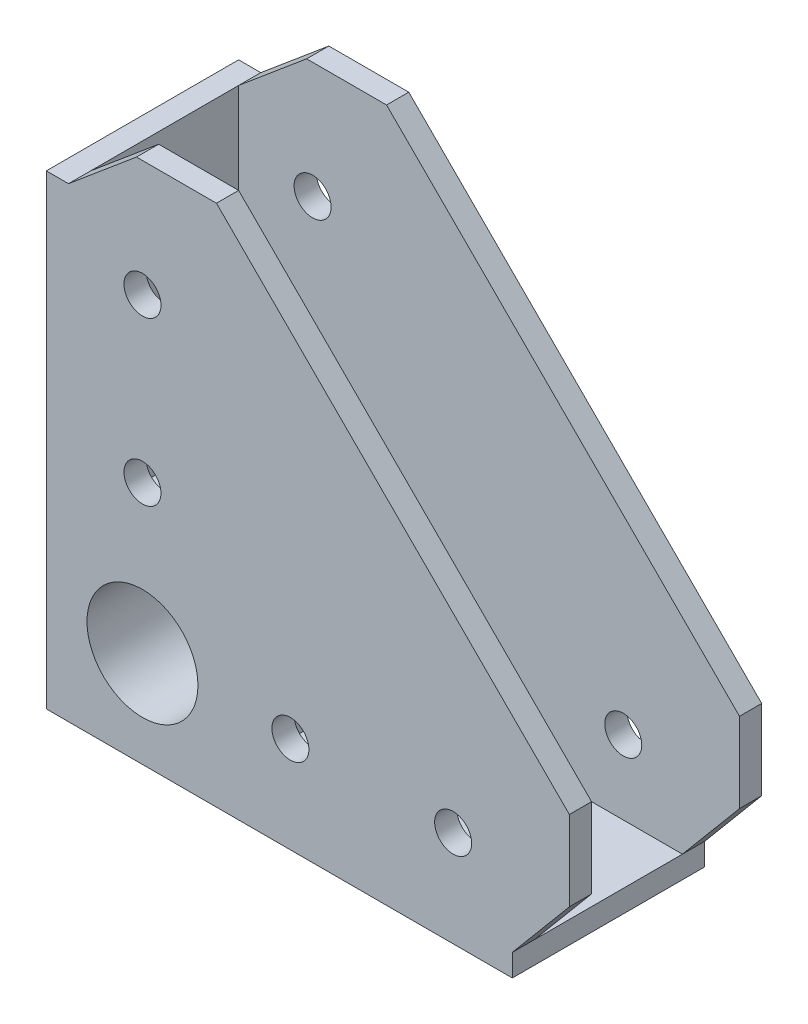
SolidWorks part; units mm, degrees
other "İşaretleme1"
sketch "Çizim10" plane through (57.7135, 57.7135, -3) normal (0.8319, 0.5548, -0.006) x (0.1401, -0.2205, -0.9653)
ref_plane "Ön Düzlem" through (0, 0, 0) normal (0, 0, 1) x (1, 0, 0)
ref_plane "Üst Düzlem" through (0, 0, 0) normal (0, 1, 0) x (1, 0, 0)
ref_plane "Sağ Düzlem" through (0, 0, 0) normal (1, 0, 0) x (0, 0, -1)
sketch "Çizim1" plane through (0, 0, 0) normal (0, 0, 1) x (1, 0, 0)
  line L0 (-21.4286, 0) -> (19.4898, 0) construction
  line L1 (0, 15.5102) -> (0, -19.1837) construction
  line L3 (-10, 10) -> (10, 10)
  line L4 (-10, 10) -> (-10, -10)
  line L5 (-10, -10) -> (10, -10)
  line L6 (10, 10) -> (10, -10)
  line L7 (-10, 10) -> (10, -10) construction
  line L8 (-10, -10) -> (10, 10) construction
  point P5 (0, 0)
  dimension "D1" = 20
  dimension "D2" = 20
extrude "Yükseklik-Ekstrüzyon1" add sketch "Çizim1" along normal blind 20
sketch "Çizim2" plane through (0, 0, 20) normal (0, 0, 1) x (1, 0, 0)
  line L0 (-10, -10) -> (-10, 10)
  line L1 (-10, 10) -> (-10, 50)
  line L2 (-10, -10) -> (10, -10)
  line L3 (10, -10) -> (50, -10)
  line L4 (-10, 50) -> (-0.8075, 57.7135)
  line L5 (50, -10) -> (57.7135, -0.8075)
  line L6 (57.7135, -0.8075) -> (57.7135, 10)
  line L7 (-0.8075, 57.7135) -> (10, 57.7135)
  line L8 (10, 57.7135) -> (57.7135, 10)
  dimension "D1" = 40
  dimension "D2" = 40
  dimension "D3" = 12
  dimension "D4" = 130
  dimension "D5" = 130
  dimension "D6" = 12
extrude "Yükseklik-Ekstrüzyon2" add sketch "Çizim2" along normal blind 3
sketch "Çizim3" plane through (0, 0, 0) normal (0, 0, -1) x (-1, 0, 0)
  line L0 (10, -10) -> (-50, -10)
  line L1 (-50, -10) -> (-57.7135, -0.8075)
  line L2 (-57.7135, -0.8075) -> (-57.7135, 10)
  line L3 (-57.7135, 10) -> (-10, 57.7135)
  line L4 (-10, 57.7135) -> (0.8075, 57.7135)
  line L5 (0.8075, 57.7135) -> (10, 50)
  line L6 (10, 50) -> (10, -10)
extrude "Yükseklik-Ekstrüzyon3" add sketch "Çizim3" along normal blind 3
sketch "Çizim4" plane through (-10, 0, 0) normal (-1, 0, 0) x (0, 0, 1)
  line L0 (-3, -10) -> (23, -10)
  line L1 (23, -10) -> (23, 50)
  line L2 (23, 50) -> (-3, 50)
  line L3 (-3, 50) -> (-3, -10)
extrude "Yükseklik-Ekstrüzyon4" add sketch "Çizim4" along normal blind 3
sketch "Çizim5" plane through (0, -10, 0) normal (0, -1, 0) x (1, 0, 0)
  line L0 (-13, 23) -> (50, 23)
  line L1 (50, 23) -> (50, -3)
  line L2 (50, -3) -> (-13, -3)
  line L3 (-13, -3) -> (-13, 23)
extrude "Yükseklik-Ekstrüzyon5" add sketch "Çizim5" along normal blind 3
sketch "Çizim6" plane through (0, 0, 23) normal (0, 0, 1) x (1, 0, 0)
  circle A0 centre (0, 0) radius 7.5
  dimension "D3" = 15
extrude "Kes-Ekstrüzyon1" cut sketch "Çizim6" against normal through all
sketch "Çizim7" plane through (0, 0, -3) normal (0, 0, -1) x (-1, 0, 0)
  circle A1 centre (-20, 0) radius 2.5
  circle A2 centre (-42, 0) radius 2.5
  circle A3 centre (0, 20) radius 2.5
  circle A4 centre (0, 42) radius 2.5
  dimension "D1" = 5
  dimension "D2" = 5
  dimension "D3" = 5
  dimension "D4" = 5
  dimension "D5" = 20
  dimension "D6" = 22
  dimension "D7" = 20
  dimension "D8" = 22
extrude "Kes-Ekstrüzyon2" cut sketch "Çizim7" against normal blind 50
sketch "Çizim8" plane through (-10, 0, 0) normal (1, 0, 0) x (0, 0, -1)
  line L0 (-20, 10) -> (0, 10) construction
  circle A0 centre (-10, 20) radius 1.9247
  circle A1 centre (-10, 42) radius 2.2237
  dimension "D1" = 10
  dimension "D2" = 22
extrude "Kes-Ekstrüzyon3" cut sketch "Çizim8" against normal blind 50
sketch "Çizim9" plane through (0, -10, 0) normal (0, 1, 0) x (1, 0, 0)
  line L0 (10, -20) -> (10, 0) construction
  circle A0 centre (20, -10) radius 1.7946
  circle A1 centre (42, -10) radius 1.8164
  dimension "D1" = 10
  dimension "D2" = 22
extrude "Kes-Ekstrüzyon4" cut sketch "Çizim9" against normal blind 50
